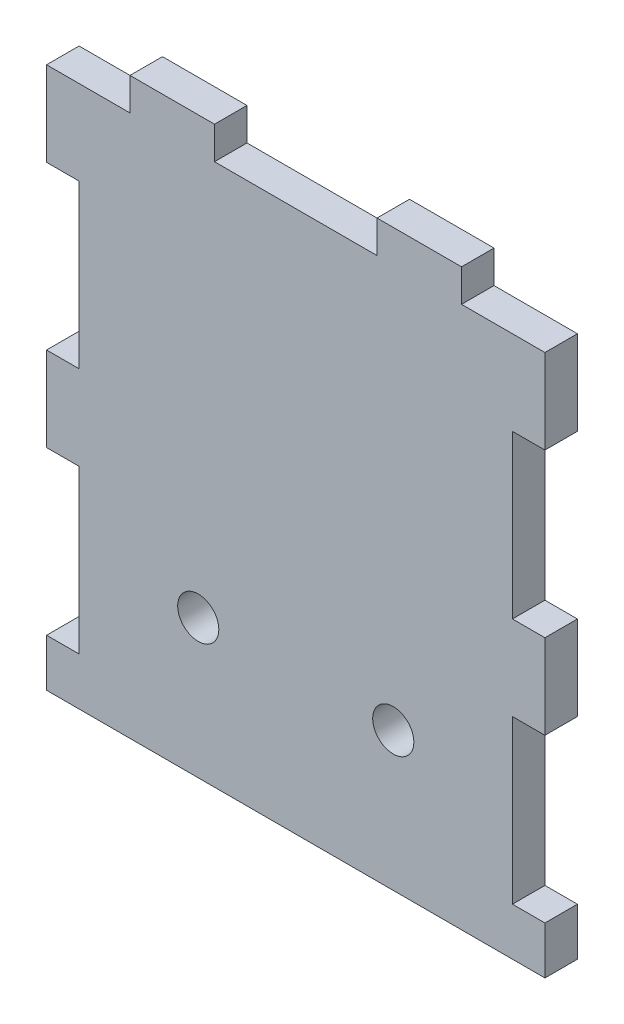
SolidWorks part; units mm, degrees
material "Oak"
ref_plane "Front Plane" through (0, 0, 0) normal (0, 0, 1) x (1, 0, 0)
ref_plane "Top Plane" through (0, 0, 0) normal (0, 1, 0) x (1, 0, 0)
ref_plane "Right Plane" through (0, 0, 0) normal (1, 0, 0) x (0, 0, -1)
sketch "Sketch1" plane through (0, 0, 0) normal (0, 0, 1) x (1, 0, 0)
  line L1 (-40.9935, 16.542) -> (5.0065, 16.542)
  line L2 (-40.9935, 16.542) -> (-40.9935, -33.458)
  line L3 (-40.9935, -33.458) -> (5.0065, -33.458)
  line L4 (5.0065, 16.542) -> (5.0065, -33.458)
  dimension "D1" = 50
  dimension "D2" = 46
extrude "Boss-Extrude1" add sketch "Sketch1" along normal blind 3
sketch "Sketch2" plane through (0, 0, 3) normal (0, 0, 1) x (1, 0, 0)
  line L0 (-40.9935, 16.542) -> (-40.9935, -33.458) construction
  line L1 (-40.9935, 8.742) -> (-37.9935, 8.742)
  line L2 (-40.9935, 8.742) -> (-40.9935, -6.258)
  line L3 (-40.9935, -6.258) -> (-37.9935, -6.258)
  line L4 (-37.9935, 8.742) -> (-37.9935, -6.258)
  line L5 (5.0065, 16.542) -> (-40.9935, 16.542) construction
  line L6 (5.0065, -33.458) -> (5.0065, 16.542) construction
  line L7 (5.0065, 8.742) -> (2.0065, 8.742)
  line L8 (5.0065, 8.742) -> (5.0065, -6.258)
  line L9 (5.0065, -6.258) -> (2.0065, -6.258)
  line L10 (2.0065, 8.742) -> (2.0065, -6.258)
  point P8 (-39.4935, 8.742)
  dimension "D1" = 3
  dimension "D2" = 7.8
  dimension "D3" = 15
  dimension "D4" = 3
  dimension "D5" = 7.8
  dimension "D6" = 15
extrude "Cut-Extrude1" cut sketch "Sketch2" against normal through all
pattern_linear "LPattern1" count 3 spacing 22.8 along (0, -1, 0) of "Cut-Extrude1"
sketch "Sketch3" plane through (0, 16.542, 0) normal (0, 1, 0) x (1, 0, 0)
  line L0 (5.0065, 0) -> (-40.9935, 0) construction
  line L1 (-33.2935, 0) -> (-25.4935, 0)
  line L2 (-33.2935, 0) -> (-33.2935, -3)
  line L3 (-33.2935, -3) -> (-25.4935, -3)
  line L4 (-25.4935, 0) -> (-25.4935, -3)
  line L5 (5.0065, -3) -> (-40.9935, -3) construction
  line L6 (-40.9935, -3) -> (-40.9935, 0) construction
  point P8 (-25.4935, -1.5)
  dimension "D1" = 7.8
  dimension "D2" = 7.7
extrude "Boss-Extrude2" add sketch "Sketch3" along normal blind 3
pattern_linear "LPattern2" count 2 spacing 22.8 along (1, 0, 0) of "Boss-Extrude2"
hole_wizard "#6 Clearance Hole1" positions "Sketch4" profile "Sketch5" hole size "#6" standard "ANSI Inch" end condition through all
sketch "Sketch4" plane through (0, 0, 3) normal (0, 0, 1) x (1, 0, 0)
  point P0 (-8.9935, -20.658)
  point P3 (-26.9935, -20.658)
  point P8 (0, 0)
sketch "Sketch5" plane through (-8.9935, -20.658, 3) normal (1, 0, 0) x (0, -1, 0)
  line L0 (0, 0) -> (0, 3)
  line L1 (0, 3) -> (1.8986, 3)
  line L2 (1.8986, 3) -> (1.8986, 0)
  line L5 (1.8986, 0) -> (0, 0)
  line L11 (0, -6.35) -> (0, 107.95) construction
  dimension "Thru Hole Dia." = 3.7973
  dimension "Thru Hole Depth" = 3
